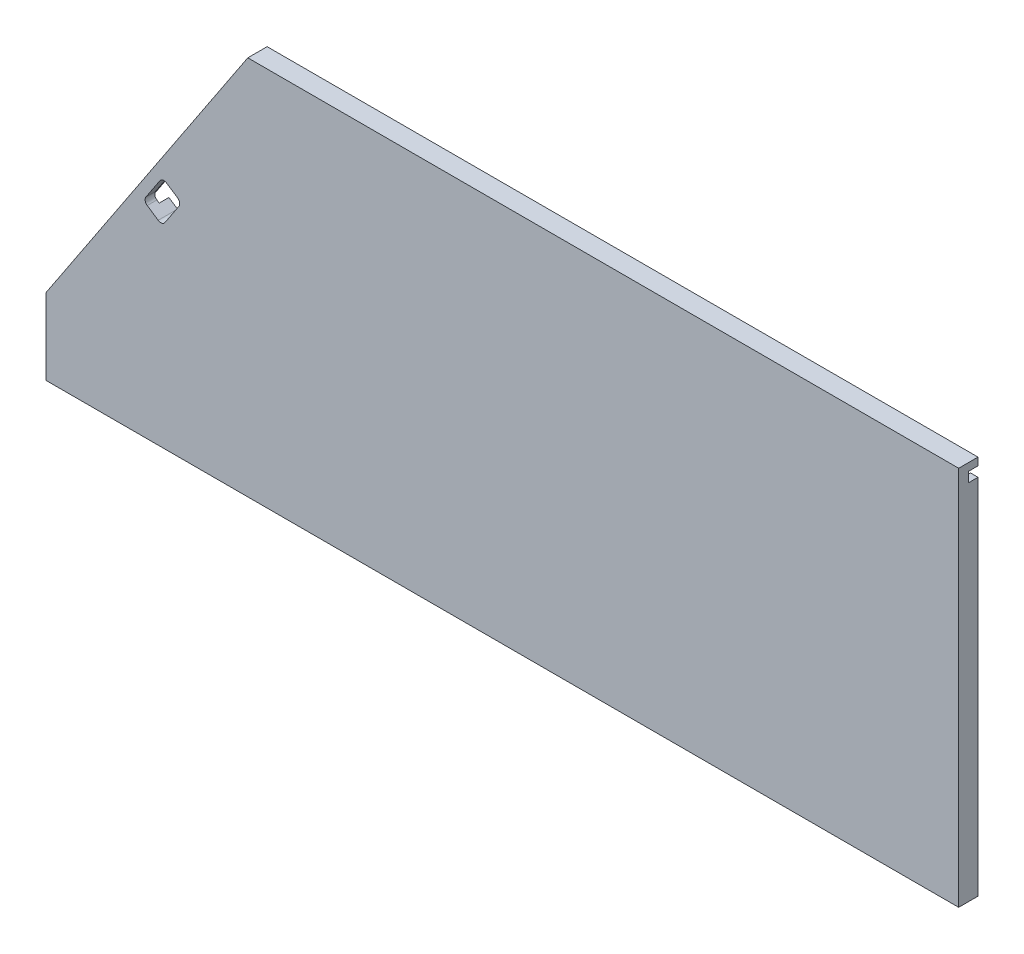
SolidWorks part; units mm, degrees
ref_plane "Front Plane" through (0, 0, 0) normal (0, 0, 1) x (1, 0, 0)
ref_plane "Top Plane" through (0, 0, 0) normal (0, 1, 0) x (1, 0, 0)
ref_plane "Right Plane" through (0, 0, 0) normal (1, 0, 0) x (0, 0, -1)
sketch "Sketch1" plane through (0, 0, 0) normal (0, 0, 1) x (1, 0, 0)
  line L0 (-524.5299, -25.692) -> (75.4701, -25.692)
  line L1 (75.4701, -25.692) -> (75.4701, 224.308)
  line L2 (75.4701, 224.308) -> (-391.8649, 224.308)
  line L3 (-391.8649, 224.308) -> (-524.5299, 24.308)
  line L4 (-524.5299, 24.308) -> (-524.5299, -25.692)
  dimension "D1" = 50
  dimension "D2" = 250
  dimension "D3" = 600
  dimension "D4" = 240
extrude "Boss-Extrude1" add sketch "Sketch1" along normal blind 12.7
sketch "Sketch4" plane through (0, 0, 0) normal (0, 0, 1) x (1, 0, 0)
  line L5 (-513.0299, 20.8407) -> (-513.0299, -14.192)
  line L6 (-513.0299, -14.192) -> (63.9701, -14.192)
  line L7 (63.9701, -14.192) -> (63.9701, 212.808)
  line L8 (63.9701, 212.808) -> (-385.6931, 212.808)
  line L9 (-385.6931, 212.808) -> (-513.0299, 20.8407)
  line L10 (-519.5299, 22.8005) -> (-519.5299, -20.692)
  line L11 (-519.5299, -20.692) -> (70.4701, -20.692)
  line L12 (70.4701, -20.692) -> (70.4701, 219.308)
  line L13 (70.4701, 219.308) -> (-389.1815, 219.308)
  line L14 (-389.1815, 219.308) -> (-519.5299, 22.8005)
  line L15 (-519.5299, 22.8005) -> (-519.5299, -20.692)
  line L16 (-519.5299, -20.692) -> (70.4701, -20.692)
  line L17 (70.4701, -20.692) -> (70.4701, 219.308)
  line L18 (70.4701, 219.308) -> (-389.1815, 219.308)
  line L19 (-389.1815, 219.308) -> (-519.5299, 22.8005)
  dimension "D1" = 5
  dimension "D2" = 6.5
extrude "Cut-Extrude2" cut sketch "Sketch4" along normal blind 6.35
sketch "Sketch6" plane through (0, 0, 0) normal (0, 0, -1) x (-1, 0, 0)
  line L0 (443.7341, 125.308) -> (435.4007, 119.7803)
  line L1 (385.6931, 212.808) -> (513.0299, 20.8407) construction
  line L2 (435.4007, 119.7803) -> (448.1145, 100.6137)
  line L3 (448.1145, 100.6137) -> (456.4478, 106.1414)
  line L4 (385.6931, 212.808) -> (513.0299, 20.8407) construction
  line L6 (443.7341, 125.308) -> (447.9007, 128.0719)
  line L7 (447.9007, 128.0719) -> (460.6145, 108.9052)
  line L8 (460.6145, 108.9052) -> (456.4478, 106.1414)
  line L9 (389.1815, 219.308) -> (519.5299, 22.8005) construction
  dimension "D1" = 5
  dimension "D2" = 10
  dimension "D3" = 23
  dimension "D4" = 105
extrude "Cut-Extrude3" cut sketch "Sketch6" against normal through all
fillet "Fillet1" radius 3.175 4 edges at (-448.1145, 100.6137, 6.35) (-435.4007, 119.7803, 6.35) (-447.9007, 128.0719, 9.525) (-460.6145, 108.9052, 9.525)
sketch "Sketch7" plane through (0, 0, 0) normal (0, 0, -1) x (-1, 0, 0)
  line L0 (-63.9701, 212.808) -> (385.6931, 212.808) construction
  line L1 (19.1346, 212.808) -> (-91.3835, 212.808)
  line L2 (19.1346, 212.808) -> (19.1346, 219.308)
  line L3 (19.1346, 219.308) -> (-91.3835, 219.308)
  line L4 (-91.3835, 212.808) -> (-91.3835, 219.308)
extrude "Cut-Extrude4" cut sketch "Sketch7" against normal up to surface (6.35 mm away) up to face at (-257.4602, 84.0065, 6.35)
